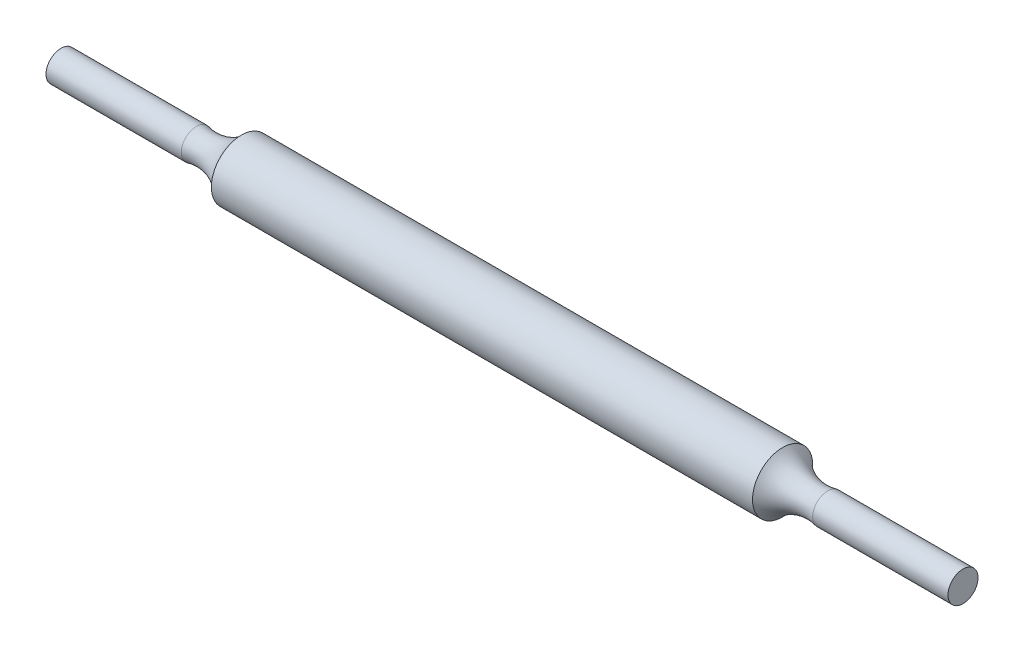
SolidWorks part; units mm, degrees
ref_plane "Front Plane" through (0, 0, 0) normal (0, 0, 1) x (1, 0, 0)
ref_plane "Top Plane" through (0, 0, 0) normal (0, 1, 0) x (1, 0, 0)
ref_plane "Right Plane" through (0, 0, 0) normal (1, 0, 0) x (0, 0, -1)
sketch "Sketch4" plane through (0, 0, 0) normal (0, 1, 0) x (1, 0, 0)
  line L1 (-30, 0) -> (30, 0)
  line L2 (30, 0) -> (30, 1)
  line L3 (30, 1) -> (21, 1)
  line L4 (-18, 2) -> (18, 2)
  line L5 (-30, 1) -> (-21, 1)
  line L6 (-30, 0) -> (-30, 1)
  line L7 (-30, 1) -> (-21, 1)
  arc A2 (18, 2) -> (21, 1) centre (20.3062, 3.9187) ccw
  arc A4 (-18, 2) -> (-21, 1) centre (-20.3062, 3.9187) cw
  point P9 (18, 2)
  point P10 (20.3062, 3.9187)
  point P11 (20.3062, 3.9187)
  point P13 (21, 1)
  point P14 (0, 2)
  point P17 (0, 0)
  dimension "D1" = 30
  dimension "D2" = 1
  dimension "D3" = 9
  dimension "D4" = 3
  dimension "D5" = 2
revolve "Revolve1" add sketch "Sketch4" angle 360 about L1
